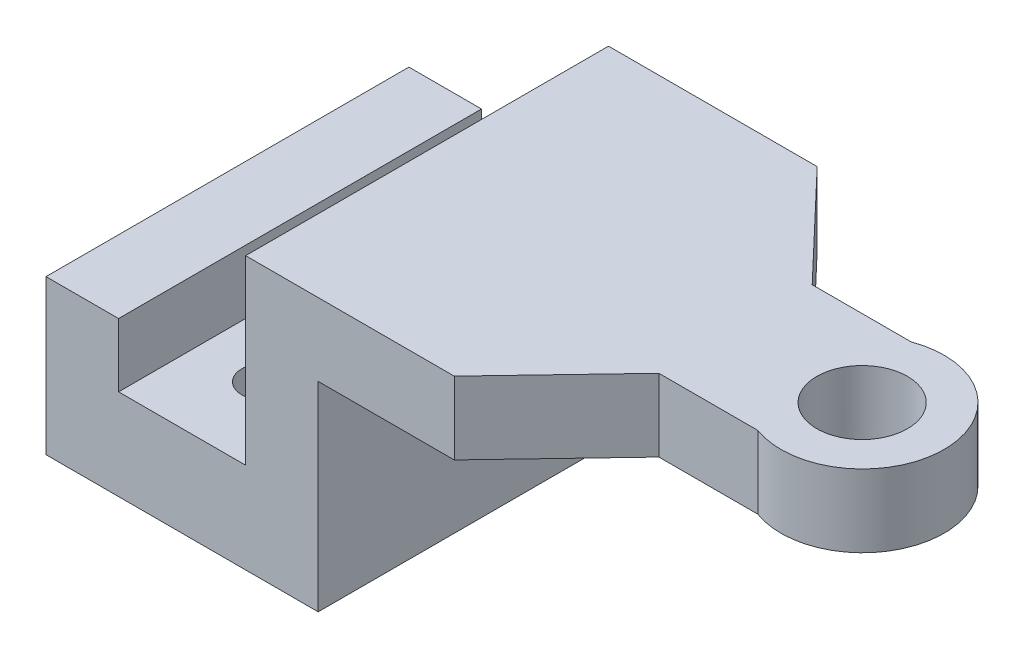
SolidWorks part; units mm, degrees
ref_plane "Front Plane" through (0, 0, 0) normal (0, 0, 1) x (1, 0, 0)
ref_plane "Top Plane" through (0, 0, 0) normal (0, 1, 0) x (1, 0, 0)
ref_plane "Right Plane" through (0, 0, 0) normal (1, 0, 0) x (0, 0, -1)
sketch "Sketch2" plane through (0, 0, 0) normal (0, 1, 0) x (1, 0, 0)
  line L0 (0, 0) -> (0, 200)
  line L1 (0, 200) -> (225, 200)
  line L3 (0, 0) -> (225, 0)
  line L6 (225, 0) -> (280, 57.7534)
  line L7 (280, 57.7534) -> (334.5007, 57.7534)
  line L8 (225, 200) -> (280, 142.2466)
  line L9 (280, 142.2466) -> (334.5007, 142.2466)
  arc A0 (334.5007, 142.2466) -> (334.5007, 57.7534) centre (350, 100) cw
  circle A1 centre (75, 155) radius 25
  circle A2 centre (75, 45) radius 25
  circle A3 centre (75, 45) radius 12.5
  circle A4 centre (75, 155) radius 12.5
  circle A5 centre (350, 100) radius 25
  dimension "D2" = 25
  dimension "D3" = 50
  dimension "D4" = 45
  dimension "D1" = 225
  dimension "D5" = 75
  dimension "D6" = 280
  dimension "D7" = 280
  dimension "D8" = 334.5007
  dimension "D9" = 45
  dimension "D10" = 350
  dimension "D11" = 100
  dimension "D14" = 155
extrude "Boss-Extrude3" add sketch "Sketch2" along normal blind 150 contours L1 L8 L9 A0 L7 L6 L3 L0
sketch "Sketch6" plane through (0, 0, 0) normal (0, -1, 0) x (1, 0, 0)
  circle A0 centre (75, -155) radius 12.5
  circle A1 centre (75, -155) radius 25
  circle A2 centre (75.4244, -45) radius 12.5
  circle A3 centre (75.4244, -45) radius 25
extrude "Cut-Extrude3" cut sketch "Sketch6" against normal blind 50 contours A2
sketch "Sketch7" plane through (0, 0, 0) normal (0, -1, 0) x (1, 0, 0)
  circle A0 centre (75.4244, -45) radius 25
  dimension "D1" = 50
extrude "Cut-Extrude4" cut sketch "Sketch7" against normal blind 20 contours A0
sketch "Sketch8" plane through (0, 0, 0) normal (0, -1, 0) x (1, 0, 0)
  line L0 (0, 0) -> (0, -200) construction
  line L2 (0, -200) -> (225, -200) construction
  circle A0 centre (75, -155) radius 12.5
  dimension "D1" = 25
  dimension "D2" = 75
  dimension "D3" = 45
extrude "Cut-Extrude7" cut sketch "Sketch8" against normal blind 50
sketch "Sketch11" plane through (0, 0, 0) normal (0, -1, 0) x (-1, 0, 0)
  circle A0 centre (-75, 155) radius 25
  dimension "D1" = 50
extrude "Cut-Extrude8" cut sketch "Sketch11" against normal blind 20 contours A0
sketch "Sketch12" plane through (0, 0, 0) normal (0, -1, 0) x (-1, 0, 0)
  line L0 (0, 0) -> (0, 200) construction
  line L1 (0, 200) -> (-225, 200) construction
  circle A0 centre (-350, 99.7878) radius 25
  dimension "D1" = 50
  dimension "D2" = 350
  dimension "D3" = 100.2122
extrude "Cut-Extrude9" cut sketch "Sketch12" against normal blind 150
sketch "Sketch14" plane through (0, 150, 0) normal (0, 1, 0) x (1, 0, 0)
  line L0 (0, 0) -> (40, 0)
  line L1 (0, 0) -> (225, 0) construction
  line L2 (40, 0) -> (40, 200)
  line L3 (0, 200) -> (225, 200) construction
  line L4 (40, 200) -> (0, 200)
  line L5 (0, 200) -> (0, 0)
  line L6 (0, 0) -> (0, 200) construction
  dimension "D1" = 40
extrude "Cut-Extrude10" cut sketch "Sketch14" against normal blind 65
sketch "Sketch15" plane through (0, 150, 0) normal (0, 1, 0) x (1, 0, 0)
  line L0 (40, 0) -> (110, 0)
  line L1 (40, 0) -> (225, 0) construction
  line L2 (110, 0) -> (110, 200)
  line L3 (40, 200) -> (225, 200) construction
  line L4 (110, 200) -> (40, 200)
  line L5 (40, 200) -> (40, 0)
  line L6 (40, 0) -> (40, 200) construction
  dimension "D1" = 70
extrude "Cut-Extrude11" cut sketch "Sketch15" against normal blind 100
sketch "Sketch16" plane through (0, 0, 0) normal (0, -1, 0) x (1, 0, 0)
  line L0 (0, 0) -> (0, -200) construction
  line L1 (0, -200) -> (225, -200) construction
  line L2 (150, -200) -> (150, 0)
  line L3 (0, 0) -> (225, 0) construction
  line L4 (150, 0) -> (225, 0)
  line L5 (225, 0) -> (280, -57.7534)
  line L6 (280, -57.7534) -> (334.5007, -57.7534)
  line L7 (150, -200) -> (225, -200)
  line L8 (225, -200) -> (280, -142.2466)
  line L9 (280, -142.2466) -> (334.5007, -142.2466)
  arc A0 (334.5007, -57.7534) -> (334.5007, -142.2466) centre (350, -100) cw
  dimension "D1" = 45
  dimension "D2" = 150
extrude "Cut-Extrude12" cut sketch "Sketch16" against normal blind 110
